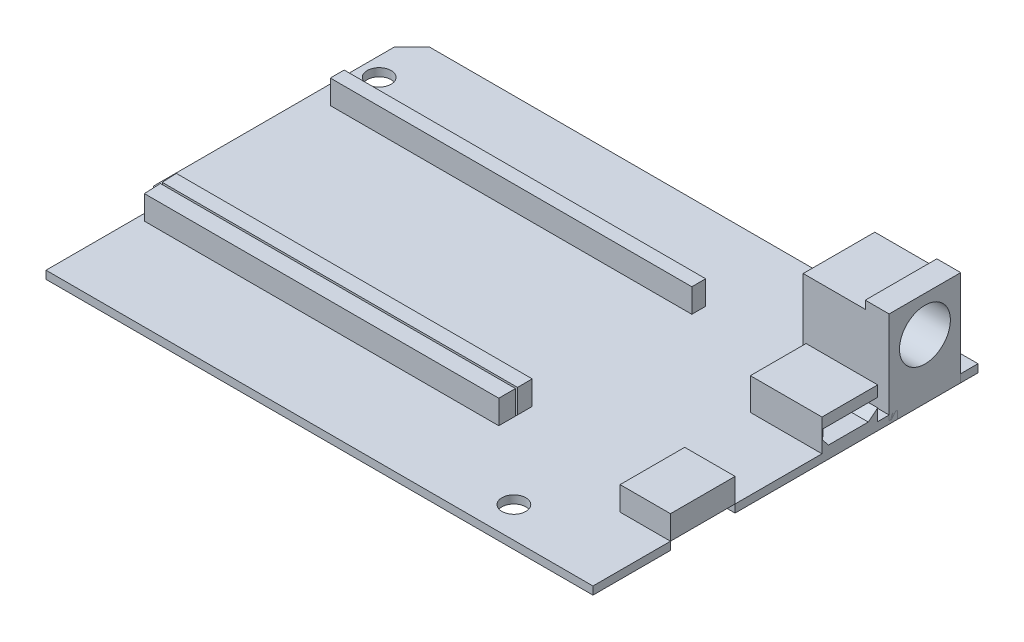
SolidWorks part; units mm, degrees
ref_plane "Front" through (0, 0, 0) normal (0, 0, 1) x (1, 0, 0)
ref_plane "Top" through (0, 0, 0) normal (0, 1, 0) x (1, 0, 0)
ref_plane "Right" through (0, 0, 0) normal (1, 0, 0) x (0, 0, -1)
sketch "Croquis2" plane through (0, 0, 0) normal (0, 1, 0) x (1, 0, 0)
  line L0 (-19.9498, 97.1711) -> (208.1221, 97.1711) construction
  line L1 (-183.1773, 45.3508) -> (-185.3464, 43.1818)
  line L2 (-114.206, 45.3508) -> (-114.206, -3.0359)
  line L3 (-114.206, -3.0359) -> (-182.9443, -3.0359)
  line L4 (-182.9443, -3.0359) -> (-182.9443, 10.4962)
  line L5 (-182.9443, 10.4962) -> (-185.3464, 12.8983)
  line L6 (-185.3464, 12.8983) -> (-185.3464, 43.1818)
  line L7 (-183.1773, 45.3508) -> (-114.206, 45.3508)
  line L8 (-182.2891, 12.6894) -> (-182.0968, 8.4834)
  line L9 (-182.9941, 34.4836) -> (-137.5639, 34.4836)
  line L10 (-182.9941, 34.4836) -> (-182.9941, 32.743)
  line L11 (-182.9941, 32.743) -> (-137.5639, 32.743)
  line L12 (-137.5639, 34.4836) -> (-137.5639, 32.743)
  line L13 (-182.2891, 12.6894) -> (-137.5639, 12.6894)
  line L14 (-182.9443, 10.4962) -> (-182.9443, 8.4834)
  line L15 (-182.0968, 8.4834) -> (-137.5639, 8.4834)
  line L16 (-137.5639, 12.6894) -> (-137.5639, 8.4834)
  line L17 (-120.5359, 14.8221) -> (-114.206, 14.8221)
  line L18 (-120.5359, 14.8221) -> (-120.5359, 6.7039)
  line L19 (-120.5359, 6.7039) -> (-114.206, 6.7039)
  line L20 (-114.206, 14.8221) -> (-114.206, 6.7039)
  line L21 (-118.6351, 32.743) -> (-114.206, 32.743)
  line L22 (-118.6351, 32.743) -> (-118.6351, 25.8224)
  line L23 (-118.6351, 25.8224) -> (-114.206, 25.8224)
  line L24 (-114.206, 32.743) -> (-114.206, 25.8224)
  line L25 (-125.1002, 43.1818) -> (-114.206, 43.1818)
  line L26 (-125.1002, 43.1818) -> (-125.1002, 35.2257)
  line L27 (-125.1002, 35.2257) -> (-114.206, 35.2257)
  line L28 (-114.206, 43.1818) -> (-114.206, 35.2257)
  line L29 (-182.193, 10.5864) -> (-137.5639, 10.5864)
  circle A0 centre (-127.0707, 43.6839) radius 1.5
  circle A1 centre (-128.0373, 0.8558) radius 1.5
  circle A2 centre (-182.9941, 38.8858) radius 1.5
  circle A3 centre (-183.1867, 14.1697) radius 1.5
  dimension "D1" = 3
extrude "Saliente-Extruir2" add sketch "Croquis2" along normal blind 1 contours L27 L26 L25 L2 L7 L1 L6 L5 L4 L3 L19 L18 L17 L23 L22 L21 A3 A2 A1 A0 L9 L12 L11 L10 L13 L16 L15 L8
sketch "Croquis3" plane through (0, 1, 0) normal (0, 1, 0) x (1, 0, 0)
  line L1 (-114.206, 43.1818) -> (-125.006, 43.1818)
  line L2 (-114.206, 43.1818) -> (-114.206, 34.1818)
  line L3 (-114.206, 34.1818) -> (-125.006, 34.1818)
  line L4 (-125.006, 43.1818) -> (-125.006, 34.1818)
  point P4 (-125.006, 38.6818)
  dimension "D1" = 9
  dimension "D2" = 10.8
extrude "Saliente-Extruir5" add sketch "Croquis3" along normal blind 11 and the other way blind 1 separate body
sketch "Croquis4" plane through (-114.206, 0, 0) normal (1, 0, 0) x (0, 0, -1)
  line L0 (45.3508, 1) -> (43.1818, 1) construction
  line L1 (34.1818, 0) -> (34.1818, 12) construction
  circle A0 centre (38.6818, 7.5) radius 3.2
  dimension "D1" = 6.5
  dimension "D3" = 6.4
  dimension "D2" = 4.5
extrude "Cortar-Extruir1" cut sketch "Croquis4" against normal blind 5
sketch "Croquis5" plane through (0, 12, 0) normal (0, 1, 0) x (1, 0, 0)
  line L0 (-117.206, 43.1818) -> (-117.206, 34.1818)
  line L4 (-114.206, 34.1818) -> (-114.206, 43.1818)
  line L5 (-114.206, 43.1818) -> (-125.006, 43.1818)
  line L6 (-125.006, 43.1818) -> (-125.006, 34.1818)
  line L7 (-125.006, 34.1818) -> (-114.206, 34.1818)
  line L8 (-114.206, 34.1818) -> (-114.206, 43.1818)
  line L9 (-114.206, 43.1818) -> (-125.006, 43.1818)
  line L10 (-125.006, 43.1818) -> (-125.006, 34.1818)
  line L11 (-125.006, 34.1818) -> (-114.206, 34.1818)
  point P6 (-117.206, 38.6818)
  line M6 (-114.206, 43.1818) -> (-125.006, 43.1818)
  line M7 (-125.006, 43.1818) -> (-125.006, 34.1818)
  line M8 (-125.006, 34.1818) -> (-114.206, 34.1818)
  dimension "D2" = 3
  dimension "D1" = 0
extrude "Cortar-Extruir2" cut sketch "Croquis5" against normal blind 1 contours L0 M6 M7 M8
sketch "Croquis6" plane through (0, 1, 0) normal (0, 1, 0) x (1, 0, 0)
  line L1 (-114.206, 32.743) -> (-123.206, 32.743)
  line L2 (-114.206, 32.743) -> (-114.206, 25.743)
  line L3 (-114.206, 25.743) -> (-123.206, 25.743)
  line L4 (-123.206, 32.743) -> (-123.206, 25.743)
  dimension "D1" = 9
  dimension "D2" = 7
extrude "Saliente-Extruir6" add sketch "Croquis6" along normal blind 4 and the other way blind 1
sketch "Croquis7" plane through (-114.206, 0, 0) normal (1, 0, 0) x (0, 0, -1)
  line L0 (25.8665, 3.6435) -> (32.7525, 3.6435)
  line L1 (32.7525, 3.6435) -> (32.7525, 2.5055)
  line L2 (32.7525, 2.5055) -> (31.5618, 1.5435)
  line L3 (31.5618, 1.5435) -> (26.5618, 1.5435)
  line L4 (26.5618, 1.5435) -> (25.8307, 2.4484)
  line L5 (25.8307, 2.4484) -> (25.8665, 3.6435)
  point P4 (26.3035, 2.5147)
  point P7 (32.7525, 3.0745)
  point P8 (24.9991, 3.8267)
  point P9 (0, 0)
  point P10 (24.9732, 3.7103)
  point P11 (24.9861, 3.7436)
  point P12 (32.5264, 2.6281)
  point P13 (25.743, 3)
  point P14 (25.9503, 2.755)
  point P15 (25.9466, 3.0515)
  point P16 (32.8326, 2.4955)
  dimension "D1" = 5
  dimension "D2" = 2.1
  dimension "D3" = 6.9
extrude "Cortar-Extruir3" cut sketch "Croquis7" against normal blind 4
sketch "Croquis8" plane through (0, 1, 0) normal (0, 1, 0) x (1, 0, 0)
  line L0 (-114.206, 6.7039) -> (-114.206, -3.0359) construction
  line L1 (-120.5359, 14.8221) -> (-114.206, 14.8221)
  line L2 (-120.5359, 14.8221) -> (-120.5359, 6.7039)
  line L3 (-120.5359, 6.7039) -> (-114.206, 6.7039)
  line L4 (-114.206, 14.8221) -> (-114.206, 6.7039)
extrude "Saliente-Extruir7" add sketch "Croquis8" along normal blind 3 separate body
sketch "Croquis9" plane through (0, 1, 0) normal (0, 1, 0) x (1, 0, 0)
  line L0 (-182.9941, 34.4836) -> (-182.9941, 32.743) construction
  line L1 (-182.9941, 32.743) -> (-137.5639, 32.743) construction
  line L2 (-182.9941, 34.4836) -> (-137.5639, 34.4836) construction
  line L3 (-137.5639, 34.4836) -> (-137.5639, 32.743) construction
  line L4 (-182.9941, 34.4836) -> (-182.9941, 32.743)
  line L5 (-137.5639, 34.4836) -> (-137.5639, 32.743)
  line L6 (-182.9941, 34.4836) -> (-137.5639, 34.4836)
  line L7 (-182.9941, 32.743) -> (-137.5639, 32.743)
  line L8 (-137.5639, 12.6894) -> (-137.5639, 8.4834) construction
  line L9 (-182.2891, 12.6894) -> (-182.0968, 8.4834) construction
  line L10 (-182.0968, 8.4834) -> (-137.5639, 8.4834) construction
  line L11 (-182.2891, 12.6894) -> (-137.5639, 12.6894) construction
  line L12 (-137.5639, 12.6894) -> (-137.5639, 8.4834)
  line L13 (-182.2891, 12.6894) -> (-182.0968, 8.4834)
  line L14 (-182.0968, 8.4834) -> (-137.5639, 8.4834)
  line L15 (-182.2891, 12.6894) -> (-137.5639, 12.6894)
  line L16 (-182.2043, 10.8336) -> (-137.5639, 10.8336)
  line L17 (-182.193, 10.5864) -> (-137.5639, 10.5864)
  point P2 (-182.9941, 33.6133)
  line M24 (-182.9941, 34.4836) -> (-137.5639, 34.4836)
  line M25 (-137.5639, 34.4836) -> (-137.5639, 32.743)
  line M26 (-137.5639, 32.743) -> (-182.9941, 32.743)
  line M27 (-182.9941, 32.743) -> (-182.9941, 34.4836)
  line M28 (-182.2891, 12.6894) -> (-137.5639, 12.6894)
  line M29 (-137.5639, 12.6894) -> (-137.5639, 8.4834)
  line M30 (-137.5639, 8.4834) -> (-182.0968, 8.4834)
  line M31 (-182.0968, 8.4834) -> (-182.2891, 12.6894)
extrude "Saliente-Extruir8" add sketch "Croquis9" along normal blind 3 and the other way blind 1 contours L13 L16 M29 M28 | L17 M31 M30 M29 | M24 M27 M26 M25
